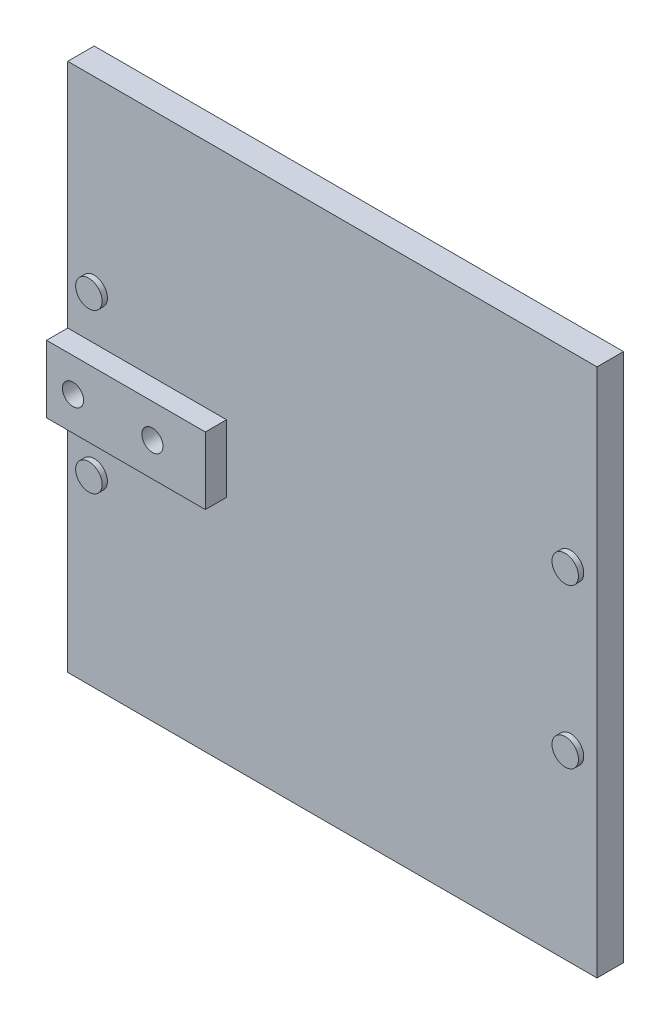
SolidWorks part; units mm, degrees
ref_plane "Front" through (0, 0, 0) normal (0, 0, 1) x (1, 0, 0)
ref_plane "Top" through (0, 0, 0) normal (0, 1, 0) x (1, 0, 0)
ref_plane "Right" through (0, 0, 0) normal (1, 0, 0) x (0, 0, -1)
sketch "Çizim1" plane through (0, 0, 0) normal (0, 0, 1) x (1, 0, 0)
  line L1 (-50, 50) -> (50, 50)
  line L2 (-50, 50) -> (-50, -50)
  line L3 (-50, -50) -> (50, -50)
  line L4 (50, 50) -> (50, -50)
  line L5 (-50, 50) -> (50, -50) construction
  line L6 (-50, -50) -> (50, 50) construction
  point P0 (0, 0)
  dimension "D1" = 100
  dimension "D2" = 100
extrude "Yükseklik-Ekstrüzyon1" add sketch "Çizim1" along normal blind 5
sketch "Çizim2" plane through (0, 0, 5) normal (0, 0, 1) x (1, 0, 0)
  line L0 (-50, 50) -> (-50, -50) construction
  line L1 (-80, 6.35) -> (-20, 6.35)
  line L2 (-80, 6.35) -> (-80, -6.35)
  line L3 (-80, -6.35) -> (-20, -6.35)
  line L4 (-20, 6.35) -> (-20, -6.35)
  line L5 (-80, 6.35) -> (-20, -6.35) construction
  line L6 (-80, -6.35) -> (-20, 6.35) construction
  line L7 (-50, 6.35) -> (-50, -6.35)
  point P0 (-50, 0)
  line M5 (-50, 50) -> (-50, -50)
  dimension "D1" = 60
  dimension "D2" = 12.7
extrude "Yükseklik-Ekstrüzyon2" add sketch "Çizim2" along normal blind 4 contours L4 L1 L3 M5
sketch "Çizim3" plane through (0, 0, 5) normal (0, 0, 1) x (1, 0, 0)
  line L0 (-50, 50) -> (-45, 50)
  line L1 (50, 50) -> (-50, 50) construction
  line L2 (-45, 50) -> (-45, 15)
  line L3 (0, 50) -> (0, -50)
  line L4 (-50, -50) -> (50, -50) construction
  line L5 (0, -50) -> (-50, 0)
  line L6 (-50, 6.35) -> (-50, -6.35) construction
  line L7 (-50, 0) -> (50, 0)
  line L8 (50, -50) -> (50, 50) construction
  circle A0 centre (-45, 15) radius 2.5
  circle A1 centre (-45, -15) radius 2.5
  circle A2 centre (45, 15) radius 2.5
  circle A3 centre (45, -15) radius 2.5
extrude "Kes-Ekstrüzyon2" cut sketch "Çizim3" against normal blind 35 and the other way through all
sketch "Çizim4" plane through (0, 0, 5) normal (0, 0, 1) x (1, 0, 0)
  circle A0 centre (-45, 15) radius 2.5
  circle A1 centre (45, 15) radius 2.5
  circle A2 centre (-45, -15) radius 2.5
  circle A3 centre (45, -15) radius 2.5
extrude "Yükseklik-Ekstrüzyon3" add sketch "Çizim4" along normal blind 1 separate body
sketch "Çizim5" plane through (0, 0, 9) normal (0, 0, 1) x (1, 0, 0)
  line L0 (-50, 0) -> (-45, 0)
  line L1 (-50, 6.35) -> (-50, -6.35) construction
  line L2 (-45, 0) -> (-30, 0)
  circle A0 centre (-45, 0) radius 2
  circle A1 centre (-30, 0) radius 2
extrude "Kes-Ekstrüzyon3" cut sketch "Çizim5" against normal up to surface (4 mm away) up to face at (-42.5, -15, 5)
